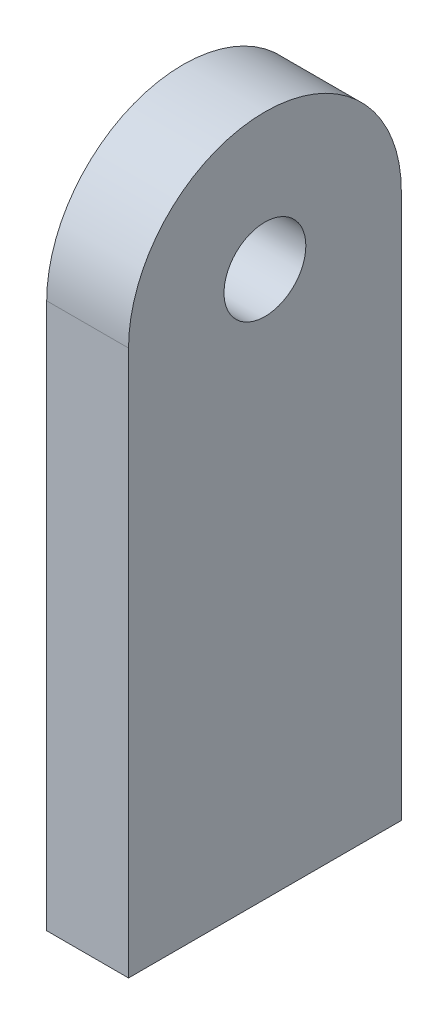
SolidWorks part; units mm, degrees
ref_plane "Front Plane" through (0, 0, 0) normal (0, 0, 1) x (1, 0, 0)
ref_plane "Top Plane" through (0, 0, 0) normal (0, 1, 0) x (1, 0, 0)
ref_plane "Right Plane" through (0, 0, 0) normal (1, 0, 0) x (0, 0, -1)
sketch "Sketch1" plane through (0, 0, 0) normal (1, 0, 0) x (0, 0, -1)
  line L0 (20, 40) -> (20, 0)
  line L1 (20, 0) -> (0, 0)
  line L2 (0, 0) -> (0, 40)
  arc A0 (0, 40) -> (20, 40) centre (10, 40) cw
  circle A1 centre (10, 40) radius 3
  dimension "D2" = 6
  dimension "D1" = 20
  dimension "D3" = 40
extrude "Boss-Extrude1" add sketch "Sketch1" along normal blind 6
